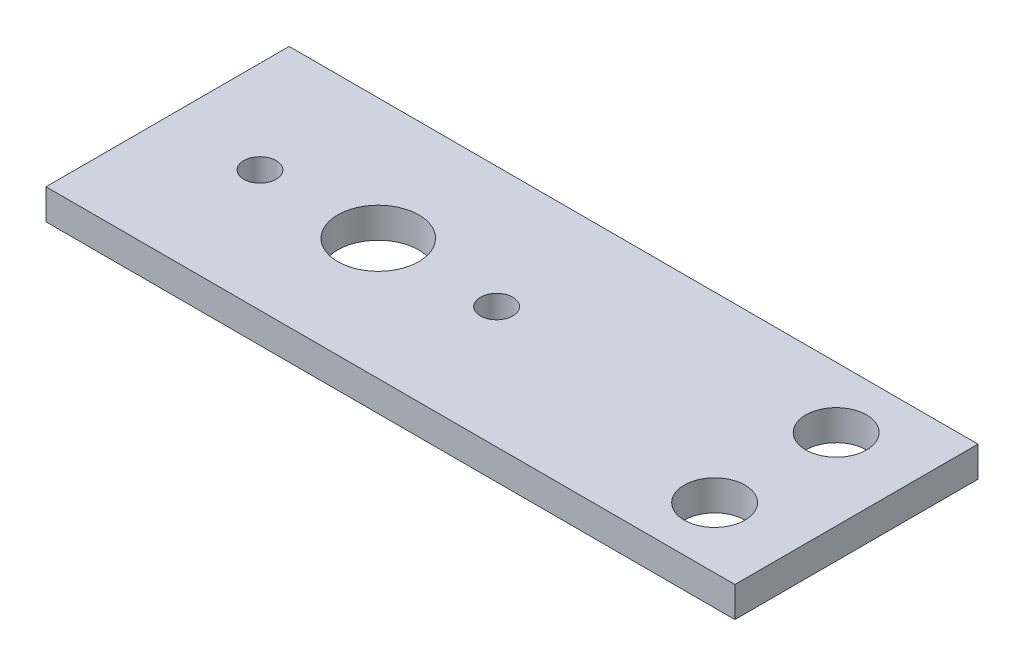
SolidWorks part; units mm, degrees
ref_plane "Front Plane" through (0, 0, 0) normal (0, 0, 1) x (1, 0, 0)
ref_plane "Top Plane" through (0, 0, 0) normal (0, 1, 0) x (1, 0, 0)
ref_plane "Right Plane" through (0, 0, 0) normal (1, 0, 0) x (0, 0, -1)
sketch "Sketch2" plane through (0, 0, 0) normal (0, 1, 0) x (1, 0, 0)
  line L1 (-53.975, -19.05) -> (53.975, -19.05)
  line L2 (-53.975, -19.05) -> (-53.975, 19.05)
  line L3 (-53.975, 19.05) -> (53.975, 19.05)
  line L4 (53.975, -19.05) -> (53.975, 19.05)
  line L5 (0, 19.05) -> (0, -19.05) construction
  line L6 (-53.975, 0) -> (53.975, 0) construction
  circle A0 centre (41.275, 9.525) radius 4.7625
  circle A1 centre (41.275, -9.525) radius 4.7625
  point P0 (0, 0)
  dimension "D3" = 9.525
  dimension "D1" = 38.1
  dimension "D2" = 107.95
  dimension "D4" = 9.525
  dimension "D5" = 12.7
extrude "Boss-Extrude1" add sketch "Sketch2" along normal blind 4.7625
sketch "Sketch3" plane through (0, 4.7625, 0) normal (0, 1, 0) x (1, 0, 0)
  line L0 (-61.7682, 0) -> (69.3065, 0) construction
  line L1 (0, 24.115) -> (0, -29.4226) construction
  line L2 (-53.975, 19.05) -> (-53.975, -19.05) construction
  circle A0 centre (-20.955, 0) radius 6.35
  circle A1 centre (-2.413, 0) radius 2.54
  circle A2 centre (-39.497, 0) radius 2.54
  dimension "D2" = 12.7
  dimension "D5" = 5.08
  dimension "D1" = 33.02
  dimension "D3" = 37.084
  dimension "D4" = 18.542
extrude "Cut-Extrude1" cut sketch "Sketch3" against normal through all contours A2 | A1 | A0
